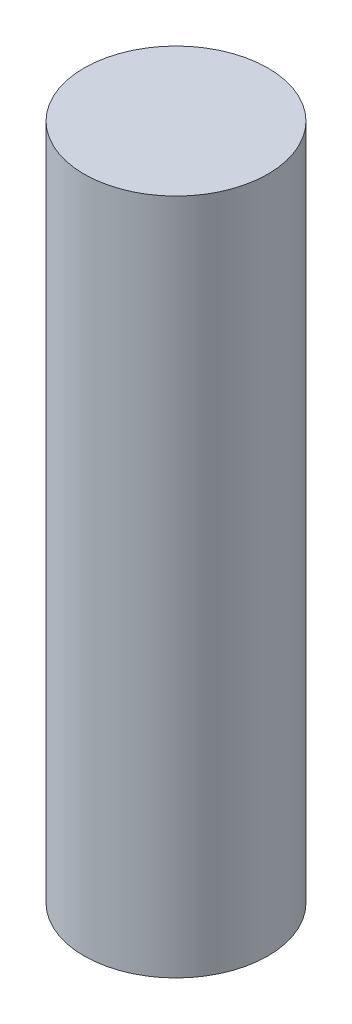
SolidWorks part; units mm, degrees
ref_plane "Plano frontal" through (0, 0, 0) normal (0, 0, 1) x (1, 0, 0)
ref_plane "Plano superior" through (0, 0, 0) normal (0, 1, 0) x (1, 0, 0)
ref_plane "Plano direito" through (0, 0, 0) normal (1, 0, 0) x (0, 0, -1)
sketch "Esboço1" plane through (0, 0, 0) normal (0, 1, 0) x (1, 0, 0)
  circle A0 centre (0, 0) radius 7.5
  dimension "D1" = 15
extrude "Ressalto-extrusão1" add sketch "Esboço1" along normal blind 55.25
